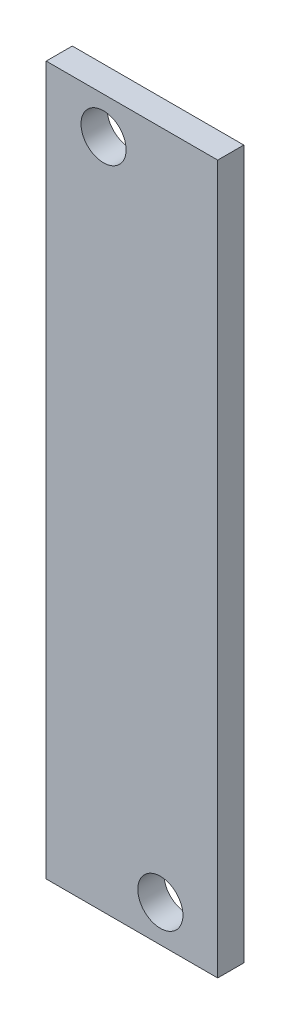
SolidWorks part; units mm, degrees
material "Custom Plastic"
ref_plane "X-Y Datum" through (0, 0, 0) normal (0, 0, 1) x (1, 0, 0)
ref_plane "X-Z Datum" through (0, 0, 0) normal (0, 1, 0) x (1, 0, 0)
ref_plane "Y-Z Datum" through (0, 0, 0) normal (1, 0, 0) x (0, 0, -1)
sketch "Sketch1" plane through (0, 0, 0) normal (0, 0, 1) x (1, 0, 0)
  line L0 (0, 42.5513) -> (0, -42.5513) construction
  line L1 (-11.5, 47.5) -> (11.5, 47.5)
  line L2 (-11.5, 47.5) -> (-11.5, -47.5)
  line L3 (-11.5, -47.5) -> (11.5, -47.5)
  line L4 (11.5, 47.5) -> (11.5, -47.5)
  line L5 (-11.5, 47.5) -> (11.5, -47.5) construction
  line L6 (-11.5, -47.5) -> (11.5, 47.5) construction
  line L7 (-3.81, 42.5513) -> (3.81, 42.5513)
  line L8 (-3.81, -42.5513) -> (3.81, -42.5513)
  circle A0 centre (-3.81, 42.5513) radius 3.025
  circle A1 centre (3.81, -42.5513) radius 3.025
  point P0 (0, 0)
  point P9 (0, 0)
  point P12 (0, 42.5513)
  point P15 (0, -42.5513)
  dimension "D5" = 6.05
  dimension "D1" = 95
  dimension "D2" = 23
  dimension "D3" = 85.1027
  dimension "D4" = 7.62
extrude "Boss-Extrude1" add sketch "Sketch1" along normal blind 3.5
